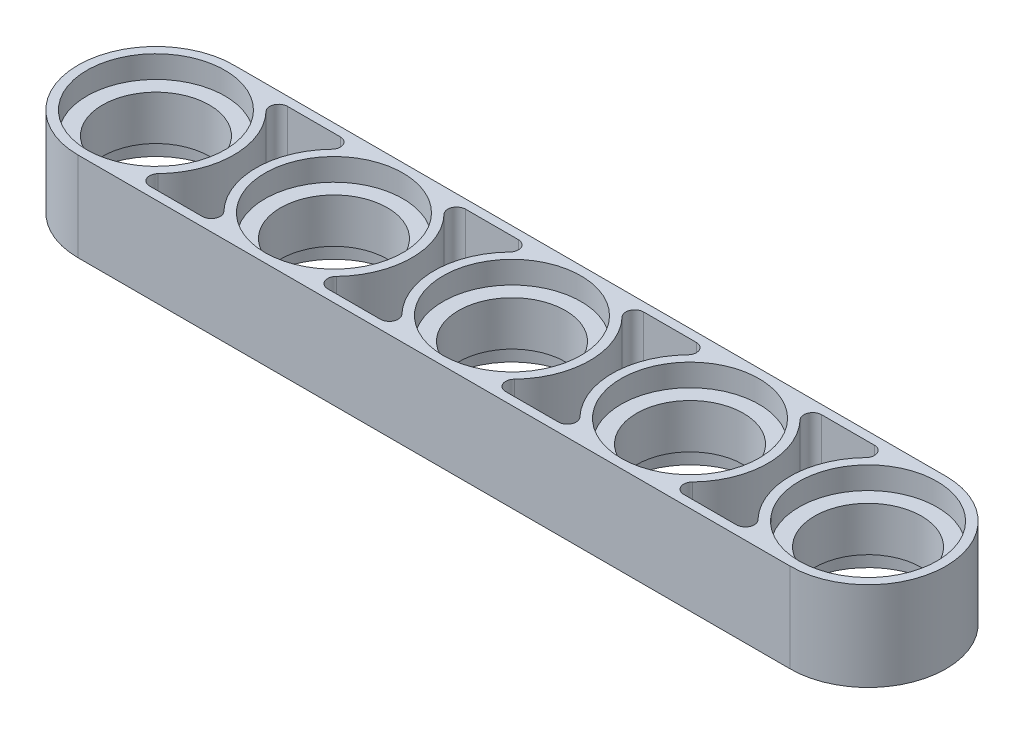
SolidWorks part; units mm, degrees
ref_plane "Front Plane" through (0, 0, 0) normal (0, 0, 1) x (1, 0, 0)
ref_plane "Top Plane" through (0, 0, 0) normal (0, 1, 0) x (1, 0, 0)
ref_plane "Right Plane" through (0, 0, 0) normal (1, 0, 0) x (0, 0, -1)
sketch "Sketch2" plane through (0, 0, 0) normal (0, 1, 0) x (1, 0, 0)
  line L0 (0, 0) -> (32, 0) construction
  line L1 (0, 3.5) -> (32, 3.5)
  line L2 (0, -3.5) -> (32, -3.5)
  arc A0 (0, 3.5) -> (0, -3.5) centre (0, 0) ccw
  arc A1 (32, -3.5) -> (32, 3.5) centre (32, 0) ccw
  point P3 (16, 0)
  point P8 (-3.5, 0)
  point P9 (35.5, 0)
  dimension "D1" = 39
  dimension "D2" = 7
extrude "Boss-Extrude1" add sketch "Sketch2" along normal mid plane 4
sketch "Sketch3" plane through (0, 2, 0) normal (0, 1, 0) x (1, 0, 0)
  circle A0 centre (0, 0) radius 3.1
  dimension "D1" = 6.2
extrude "Cut-Extrude1" cut sketch "Sketch3" against normal blind 1
sketch "Sketch4" plane through (0, -2, 0) normal (0, -1, 0) x (-1, 0, 0)
  circle A0 centre (0, 0) radius 3.1
  dimension "D1" = 6.2
extrude "Cut-Extrude2" cut sketch "Sketch4" against normal blind 1
sketch "Sketch5" plane through (0, -2, 0) normal (0, -1, 0) x (-1, 0, 0)
  circle A0 centre (0, 0) radius 2.4
  dimension "D1" = 4.8
extrude "Cut-Extrude3" cut sketch "Sketch5" against normal through all
pattern_linear "LPattern2" count 5 spacing 8 along (1, 0, 0) of "Cut-Extrude1", "Cut-Extrude2", "Cut-Extrude3"
sketch "Sketch6" plane through (0, 0, 0) normal (0, 1, 0) x (1, 0, 0)
  line L0 (2.8142, 3.1) -> (5.1858, 3.1)
  line L1 (2.8142, -3.1) -> (5.1858, -3.1)
  arc A0 (2.5256, -2.4231) -> (2.5256, 2.4231) centre (0, 0) ccw
  arc A1 (5.4744, 2.4231) -> (5.4744, -2.4231) centre (8, 0) ccw
  arc A6 (5.4744, -2.4231) -> (5.1858, -3.1) centre (5.1858, -2.7) cw
  arc A7 (2.5256, -2.4231) -> (2.8142, -3.1) centre (2.8142, -2.7) ccw
  arc A8 (2.8142, 3.1) -> (2.5256, 2.4231) centre (2.8142, 2.7) ccw
  arc A9 (5.1858, 3.1) -> (5.4744, 2.4231) centre (5.1858, 2.7) cw
  dimension "D1" = 7
  dimension "D2" = 7
  dimension "D3" = 0.4
extrude "Cut-Extrude4" cut sketch "Sketch6" against normal through all both and the other way through all
pattern_linear "LPattern3" count 4 spacing 8 along (1, 0, 0) of "Cut-Extrude4"
